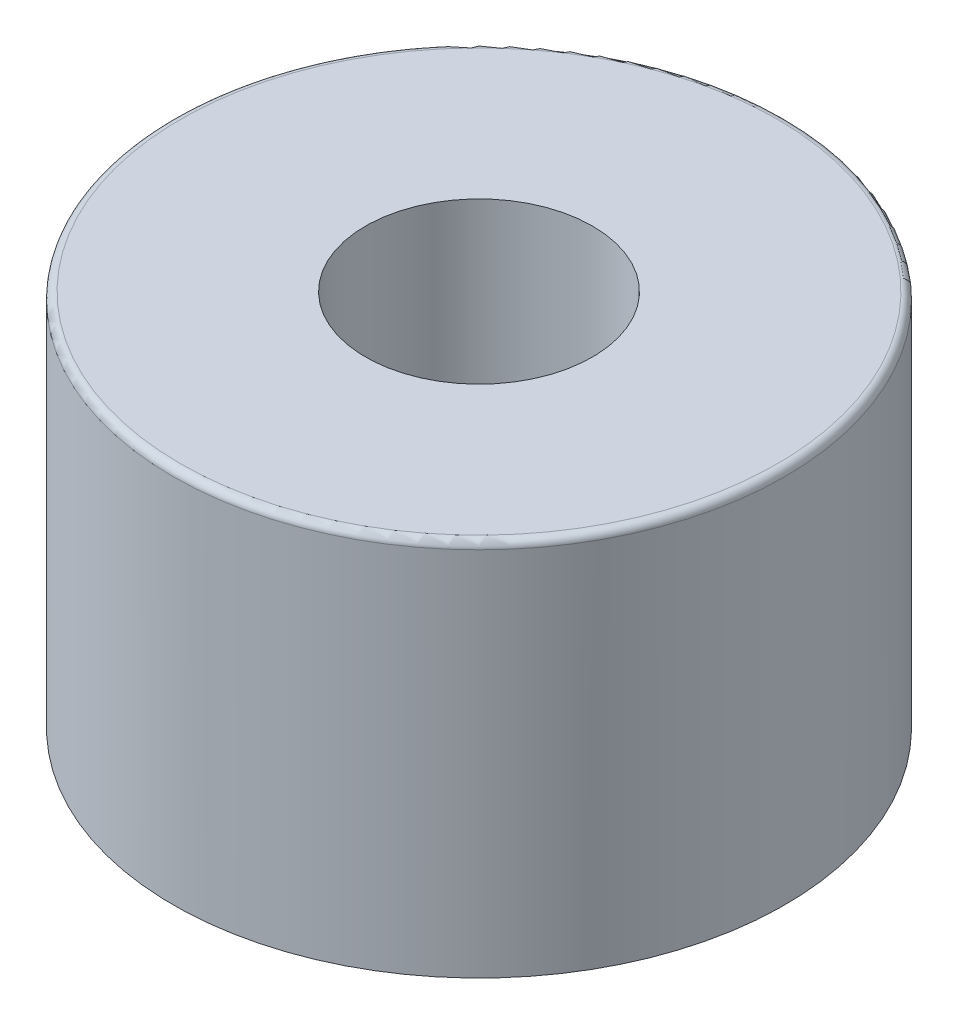
SolidWorks part; units mm, degrees
ref_plane "Front Plane" through (0, 0, 0) normal (0, 0, 1) x (1, 0, 0)
ref_plane "Top Plane" through (0, 0, 0) normal (0, 1, 0) x (1, 0, 0)
ref_plane "Right Plane" through (0, 0, 0) normal (1, 0, 0) x (0, 0, -1)
sketch "Sketch1" plane through (0, 0, 0) normal (0, 1, 0) x (1, 0, 0)
  circle A0 centre (0, 0) radius 12.319
  circle A1 centre (0, 0) radius 4.572
  dimension "D1" = 24.638
  dimension "D2" = 9.144
extrude "Boss-Extrude1" add sketch "Sketch1" along normal blind 15.24
fillet "Fillet1" radius 0.3 1 edges at (0, 15.24, 12.319)
